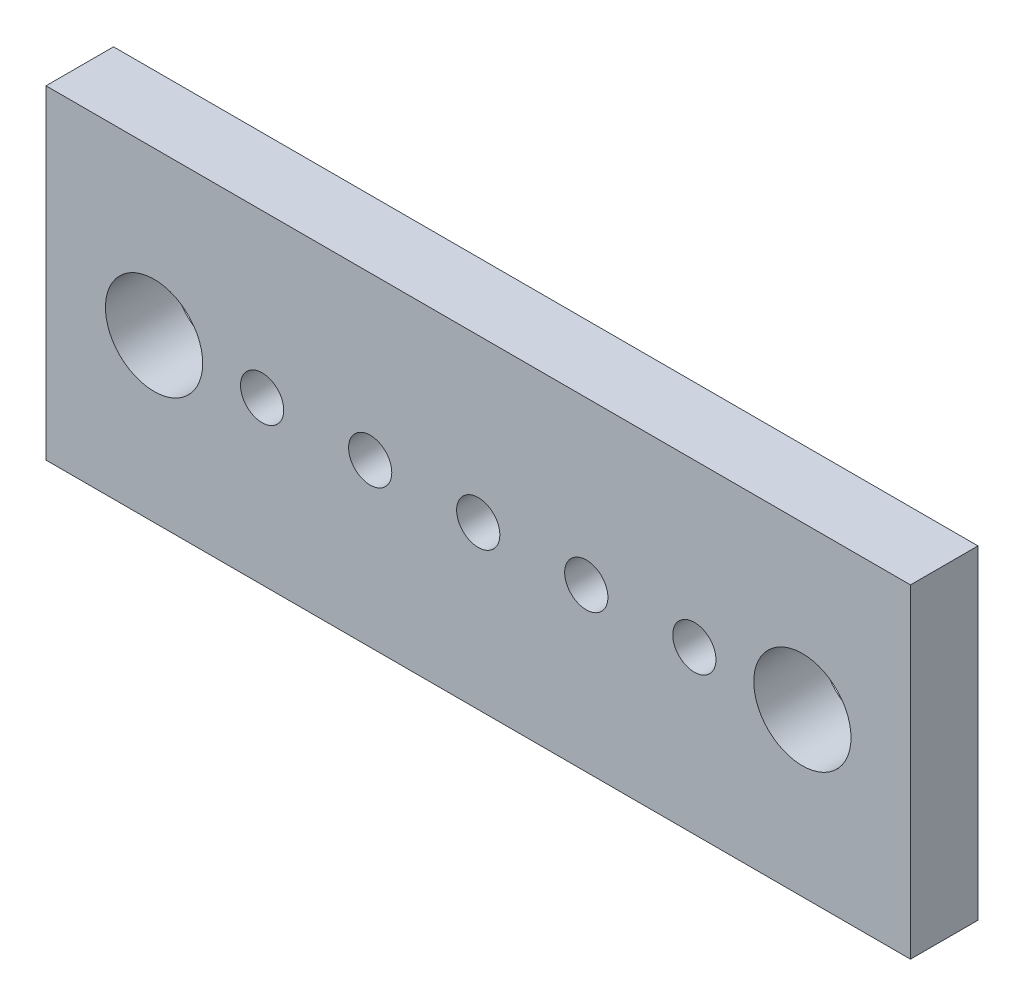
SolidWorks part; units mm, degrees
ref_plane "Front Plane" through (0, 0, 0) normal (0, 0, 1) x (1, 0, 0)
ref_plane "Top Plane" through (0, 0, 0) normal (0, 1, 0) x (1, 0, 0)
ref_plane "Right Plane" through (0, 0, 0) normal (1, 0, 0) x (0, 0, -1)
sketch "Sketch1" plane through (0, 0, 0) normal (0, 0, 1) x (1, 0, 0)
  line L0 (2.54, 3.81) -> (5.08, 3.81) construction
  line L1 (0, 0) -> (20.32, 0)
  line L2 (0, 0) -> (0, 7.62)
  line L3 (0, 7.62) -> (20.32, 7.62)
  line L4 (20.32, 0) -> (20.32, 7.62)
  line L5 (5.08, 3.81) -> (7.62, 3.81) construction
  line L6 (7.62, 3.81) -> (10.16, 3.81) construction
  line L7 (10.16, 3.81) -> (12.7, 3.81) construction
  line L8 (12.7, 3.81) -> (15.24, 3.81) construction
  line L9 (15.24, 3.81) -> (17.78, 3.81) construction
  line L10 (10.16, 3.81) -> (10.16, 7.62) construction
  line L11 (10.16, 3.81) -> (10.16, 0) construction
  circle A0 centre (2.54, 3.81) radius 0.508
  circle A1 centre (5.08, 3.81) radius 0.508
  circle A2 centre (7.62, 3.81) radius 0.508
  circle A3 centre (10.16, 3.81) radius 0.508
  circle A4 centre (12.7, 3.81) radius 0.508
  circle A5 centre (15.24, 3.81) radius 0.508
  circle A6 centre (17.78, 3.81) radius 0.508
  dimension "D3" = 1.016
  dimension "D1" = 20.32
  dimension "D2" = 7.62
  dimension "D4" = 2.54
extrude "Boss-Extrude1" add sketch "Sketch1" along normal blind 1.5875
sketch "Sketch2" plane through (0, 0, 1.5875) normal (0, 0, 1) x (1, 0, 0)
  circle A0 centre (2.54, 3.81) radius 1.143
  circle A1 centre (17.78, 3.81) radius 1.143
  dimension "D1" = 2.286
extrude "Cut-Extrude1" cut sketch "Sketch2" against normal through all
